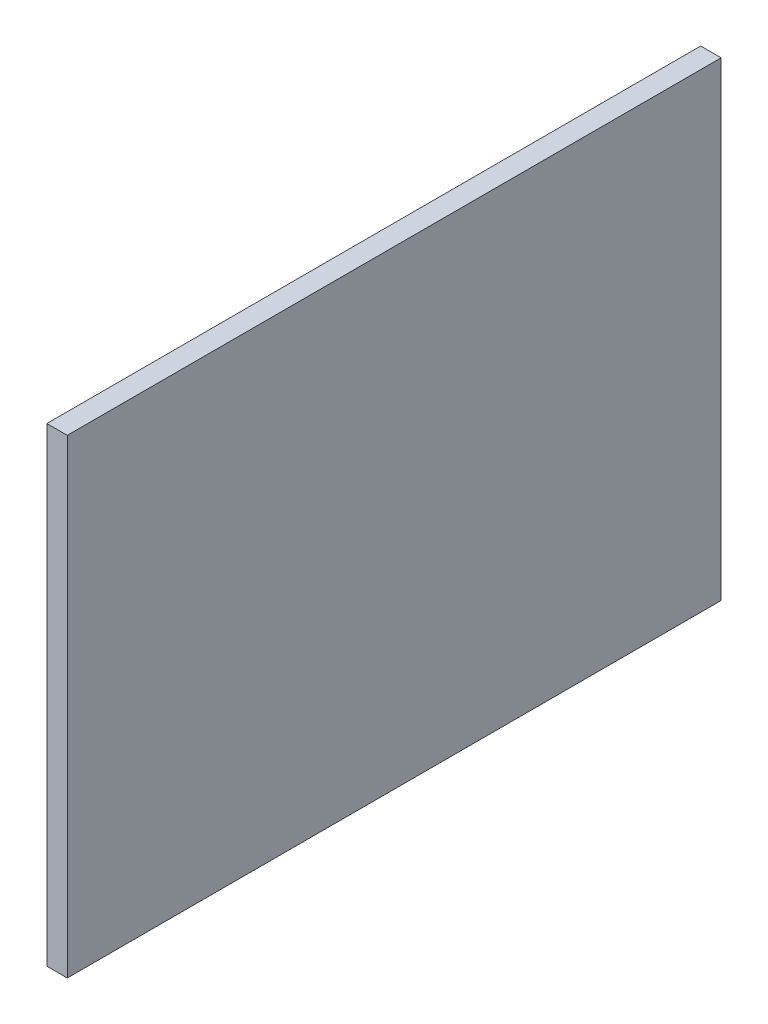
SolidWorks part; units mm, degrees
ref_plane "Спереди" through (0, 0, 0) normal (0, 0, 1) x (1, 0, 0)
ref_plane "Сверху" through (0, 0, 0) normal (0, 1, 0) x (1, 0, 0)
ref_plane "Справа" through (0, 0, 0) normal (1, 0, 0) x (0, 0, -1)
sketch "Эскиз1" plane through (0, 0, 0) normal (1, 0, 0) x (0, 0, -1)
  line L1 (-105.9417, 54.1496) -> (54.0583, 54.1496)
  line L2 (-105.9417, 54.1496) -> (-105.9417, -60.8504)
  line L3 (-105.9417, -60.8504) -> (54.0583, -60.8504)
  line L4 (54.0583, 54.1496) -> (54.0583, -60.8504)
extrude "Вытянуть1" add sketch "Эскиз1" along normal blind 5
